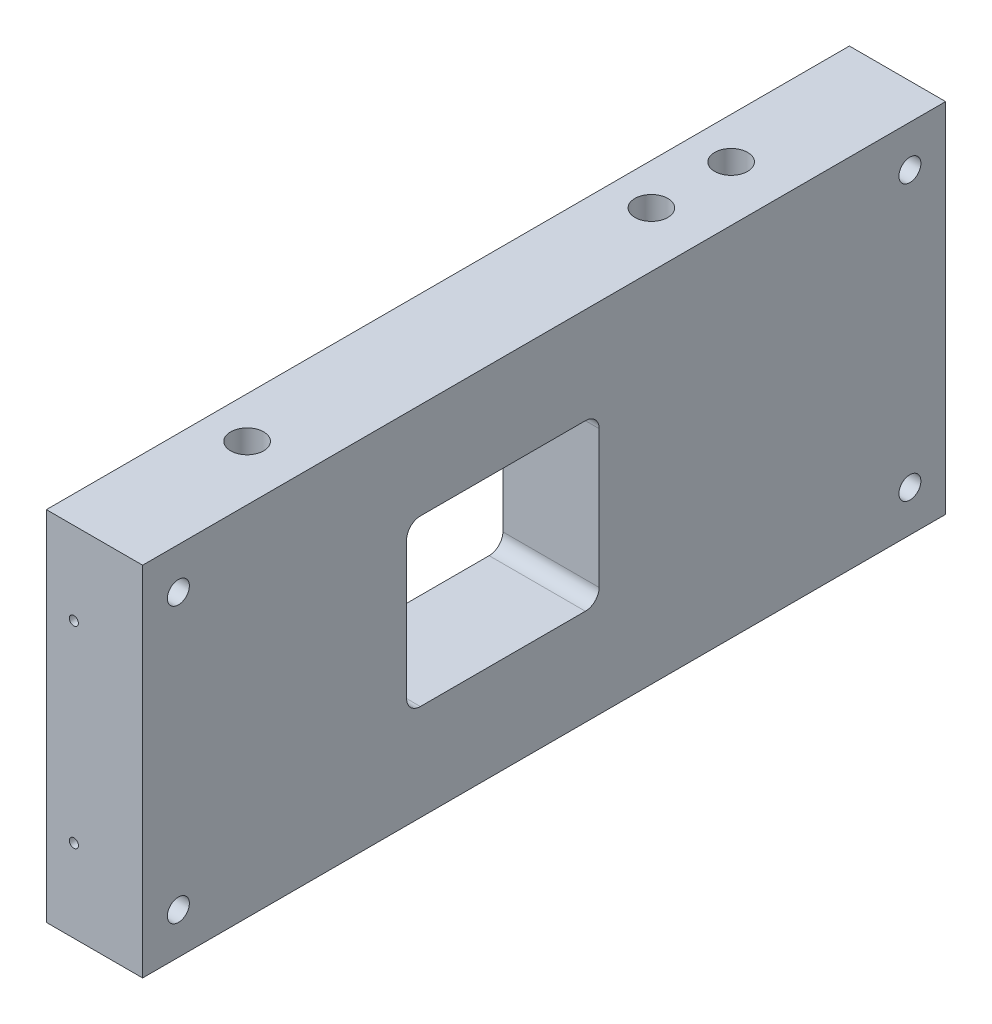
SolidWorks part; units mm, degrees
material "6063-T6"
ref_plane "Front Plane" through (0, 0, 0) normal (0, 0, 1) x (1, 0, 0)
ref_plane "Top Plane" through (0, 0, 0) normal (0, 1, 0) x (1, 0, 0)
ref_plane "Right Plane" through (0, 0, 0) normal (1, 0, 0) x (0, 0, -1)
sketch "Sketch2" plane through (0, 0, 0) normal (1, 0, 0) x (0, 0, -1)
  line L5 (0, 65) -> (191, 65)
  line L6 (0, 65) -> (0, -65)
  line L7 (0, -65) -> (191, -65)
  line L8 (191, 65) -> (191, -65)
  dimension "D1" = 65
  dimension "D2" = 130
  dimension "D3" = 191
extrude "Boss-Extrude1" add sketch "Sketch2" along normal blind 35
sketch "Sketch10" plane through (0, 0, 0) normal (0, 0, 1) x (1, 0, 0)
  line L1 (0, -65) -> (35, -65)
  line L2 (0, -65) -> (0, 65)
  line L3 (0, 65) -> (35, 65)
  line L4 (35, -65) -> (35, 65)
extrude "Boss-Extrude2" add sketch "Sketch10" along normal blind 101
sketch "Sketch4" plane through (0, 0, 0) normal (0, 0, 1) x (1, 0, 0)
  line L0 (0, 0) -> (60, 0)
  line L4 (0, 23.5) -> (8, 23.5)
  line L5 (8, 23.5) -> (8, 20)
  line L6 (8, 20) -> (18, 13.5)
  line L7 (18, 13.5) -> (22, 13.5)
  line L8 (22, 13.5) -> (22, 26)
  line L9 (22, 26) -> (27, 26)
  line L10 (27, 26) -> (27, 27)
  line L11 (27, 27) -> (51, 27)
  line L12 (51, 27) -> (51, 31)
  line L13 (51, 31) -> (60, 31)
  line L14 (0, 23.5) -> (0, 0)
  line L16 (60, 31) -> (60, 0)
  dimension "D1" = 5
  dimension "D2" = 1
  dimension "D3" = 13.5
  dimension "D4" = 26
  dimension "D5" = 29
  dimension "D6" = 8
  dimension "D7" = 3.5
  dimension "D8" = 14
  dimension "D9" = 4
  dimension "D10" = 23.5
sketch "Sketch6" plane through (0, 0, 0) normal (-1, 0, 0) x (0, 0, 1)
  point P0 (0, 0)
sketch "Sketch15" plane through (0, 0, 101) normal (0, 0, 1) x (1, 0, 0)
  line L0 (0, 65) -> (0, -65) construction
  line L1 (10, 35) -> (40, 35)
  line L2 (10, 35) -> (10, -35)
  line L3 (10, -35) -> (40, -35)
  line L4 (40, 35) -> (40, -35)
  line L5 (35, 65) -> (0, 65) construction
  line L6 (0, -65) -> (35, -65) construction
  dimension "D1" = 10
  dimension "D2" = 30
  dimension "D3" = 30
  dimension "D4" = 30
sketch "Sketch16" plane through (0, 0, -191) normal (0, 0, -1) x (-1, 0, 0)
  line L0 (-35, 65) -> (0, 65) construction
  line L1 (-40, 35) -> (-10, 35)
  line L2 (-40, 35) -> (-40, -35)
  line L3 (-40, -35) -> (-10, -35)
  line L4 (-10, 35) -> (-10, -35)
  line L5 (0, -65) -> (0, 65) construction
  line L6 (-35, -65) -> (0, -65) construction
  dimension "D1" = 30
  dimension "D2" = 30
  dimension "D3" = 10
  dimension "D4" = 30
hole_wizard "Tap Drill for M4 Tap2" positions "Sketch19" profile "Sketch20" hole size "M4" standard "ISO"
sketch "Sketch19" plane through (0, 0, -191) normal (0, 0, -1) x (-1, 0, 0)
  point P0 (-40, 35)
  point P3 (-10, 35)
  point P6 (-10, -35)
  point P9 (-40, -35)
sketch "Sketch20" plane through (40, 35, -191) normal (1, 0, 0) x (0, 1, 0)
  line L0 (0, 0) -> (0, 6.9914)
  line L1 (0, 6.9914) -> (1.65, 6)
  line L2 (1.65, 6) -> (1.65, 0)
  line L5 (1.65, 0) -> (0, 0)
  line L10 (0, 6.9914) -> (-1.65, 6) construction
  line L11 (0, -6.35) -> (0, 107.95) construction
  dimension "Hole Dia." = 3.3
  dimension "Hole Depth" = 6
  dimension "Drill Angle" = 118
hole_wizard "Tap Drill for M4 Tap3" positions "Sketch21" profile "Sketch22" hole size "M4" standard "ISO"
sketch "Sketch21" plane through (0, 0, 101) normal (0, 0, 1) x (1, 0, 0)
  point P0 (10, 35)
  point P3 (40, 35)
  point P6 (40, -35)
  point P9 (10, -35)
sketch "Sketch22" plane through (10, 35, 101) normal (1, 0, 0) x (0, -1, 0)
  line L0 (0, 0) -> (0, 6.9914)
  line L1 (0, 6.9914) -> (1.65, 6)
  line L2 (1.65, 6) -> (1.65, 0)
  line L5 (1.65, 0) -> (0, 0)
  line L10 (0, 6.9914) -> (-1.65, 6) construction
  line L11 (0, -6.35) -> (0, 107.95) construction
  dimension "Hole Dia." = 3.3
  dimension "Hole Depth" = 6
  dimension "Drill Angle" = 118
sketch "Sketch23" plane through (0, 0, 0) normal (-1, 0, 0) x (0, 0, 1)
  line L0 (-65, 25) -> (-65, -25)
  line L1 (-60, 30) -> (0, 30)
  line L2 (-60, -30) -> (0, -30)
  line L3 (5, 25) -> (5, -25)
  arc A1 (-65, -25) -> (-60, -30) centre (-60, -25) ccw
  arc A2 (0, -30) -> (5, -25) centre (0, -25) ccw
  arc A3 (0, 30) -> (5, 25) centre (0, 25) cw
  arc A4 (-60, 30) -> (-65, 25) centre (-60, 25) ccw
  point P1 (0, 0)
  dimension "D1" = 5
  dimension "D2" = 70
  dimension "D3" = 65
extrude "Cut-Extrude1" cut sketch "Sketch23" against normal through all
sketch "Sketch24" plane through (0, 0, 0) normal (-1, 0, 0) x (0, 0, 1)
  line L0 (0, 0) -> (0, 42.2578) construction
  line L1 (35, 25) -> (55, 25)
  line L2 (35, 25) -> (35, -25)
  line L3 (35, -25) -> (55, -25)
  line L4 (55, 25) -> (55, -25)
  line L5 (-55, 25) -> (-55, -25)
  line L6 (-35, -25) -> (-55, -25)
  line L7 (-35, 25) -> (-35, -25)
  line L8 (-35, 25) -> (-55, 25)
  point P4 (35, 0)
  dimension "D1" = 20
  dimension "D2" = 50
  dimension "D3" = 35
  dimension "D4" = 0
sketch "Sketch28" plane through (35, 0, 0) normal (1, 0, 0) x (0, 0, -1)
  line L0 (191, 65) -> (-101, 65) construction
  line L1 (191, -65) -> (191, 65) construction
  line L2 (-101, -65) -> (191, -65) construction
  line L3 (-101, -65) -> (-101, 65) construction
  point P0 (-88, 50)
  point P1 (-88, -50)
  point P2 (178, -50)
  point P3 (178, 50)
  point P12 (178, -50)
  dimension "D1" = 15
  dimension "D2" = 13
  dimension "D3" = 15
  dimension "D4" = 13
hole_wizard "Ø8.0mm Dowel Hole1" positions "Sketch29" profile "Sketch30" hole size "Ø8.0" standard "ISO" end condition through all
sketch "Sketch29" plane through (35, 0, 0) normal (1, 0, 0) x (0, 0, -1)
  point P0 (-88, 50)
  point P3 (-88, -50)
  point P6 (178, -50)
  point P9 (178, 50)
sketch "Sketch30" plane through (35, 50, 88) normal (0, 1, 0) x (0, 0, -1)
  line L0 (0, 0) -> (0, 35)
  line L1 (0, 35) -> (4, 35)
  line L2 (4, 35) -> (4, 0)
  line L5 (4, 0) -> (0, 0)
  line L11 (0, -6.35) -> (0, 107.95) construction
  dimension "Thru Hole Dia." = 8
  dimension "Thru Hole Depth" = 35
sketch "Sketch31" plane through (35, 0, 0) normal (1, 0, 0) x (0, 0, -1)
  line L0 (176, 25) -> (176, -25)
  line L1 (171, -30) -> (131, -30)
  line L2 (126, -25) -> (126, 25)
  line L3 (131, 30) -> (171, 30)
  line L4 (191, 35) -> (191, -35) construction
  line L5 (191, 65) -> (-101, 65) construction
  line L6 (-101, -65) -> (191, -65) construction
  line L7 (161, 50) -> (-71, 50)
  line L8 (-71, 50) -> (-71, 40)
  line L9 (-71, 40) -> (161, 40)
  line L10 (161, 40) -> (161, 50)
  line L11 (191, -65) -> (191, 65) construction
  line L12 (-101, 65) -> (-101, -65) construction
  line L13 (0, 0) -> (24.0944, 0) construction
  line L18 (161, -40) -> (161, -50)
  line L19 (-71, -40) -> (161, -40)
  line L20 (-71, -50) -> (-71, -40)
  line L21 (161, -50) -> (-71, -50)
  arc A0 (156, 50) -> (160.9957, 44.7929) centre (156, 45) cw
  arc A1 (-66, 50) -> (-66, 40) centre (-66, 45) ccw
  arc A2 (-66, -50) -> (-66, -40) centre (-66, -45) cw
  arc A3 (156, -50) -> (160.9957, -44.7929) centre (156, -45) ccw
  arc A4 (176, -25) -> (171, -30) centre (171, -25) cw
  arc A5 (131, -30) -> (126, -25) centre (131, -25) cw
  arc A6 (126, 25) -> (131, 30) centre (131, 25) cw
  arc A7 (176, 25) -> (171, 30) centre (171, 25) ccw
  point P39 (176, -30)
  point P42 (126, -30)
  point P45 (126, 30)
  point P48 (176, 30)
  dimension "D11" = 5
  dimension "D1" = 15
  dimension "D2" = 50
  dimension "D3" = 35
  dimension "D4" = 35
  dimension "D5" = 35
  dimension "D6" = 35
  dimension "D7" = 15
  dimension "D8" = 10
  dimension "D9" = 30
  dimension "D10" = 30
sketch "Sketch32" plane through (35, 0, 0) normal (1, 0, 0) x (0, 0, -1)
  line L0 (-101, 35) -> (-101, -35) construction
  line L1 (-81, 30) -> (-20, 30)
  line L2 (-86, 25) -> (-86, -25)
  line L3 (-81, -30) -> (-20, -30)
  line L4 (-15, 25) -> (-15, -25)
  line L5 (80, 30) -> (126, 30)
  line L6 (75, 25) -> (75, -25)
  line L7 (80, -30) -> (126, -30)
  line L8 (131, 25) -> (131, -25)
  line L9 (-5, -25) -> (-5, 25) construction
  line L12 (-66, 40) -> (171, 40) construction
  line L13 (-66, -40) -> (171, -40) construction
  line L15 (65, 25) -> (65, -25) construction
  line L17 (141, -25) -> (141, 25) construction
  arc A0 (75, -25) -> (80, -30) centre (80, -25) ccw
  arc A1 (126, -30) -> (131, -25) centre (126, -25) ccw
  arc A2 (126, 30) -> (131, 25) centre (126, 25) cw
  arc A3 (80, 30) -> (75, 25) centre (80, 25) ccw
  arc A4 (-86, -25) -> (-81, -30) centre (-81, -25) ccw
  arc A5 (-20, -30) -> (-15, -25) centre (-20, -25) ccw
  arc A6 (-20, 30) -> (-15, 25) centre (-20, 25) cw
  arc A7 (-81, 30) -> (-86, 25) centre (-81, 25) ccw
  point P18 (103, -30)
  dimension "D9" = 5
  dimension "D1" = 15
  dimension "D2" = 10
  dimension "D3" = 10
  dimension "D4" = 10
  dimension "D5" = 10
  dimension "D6" = 10
  dimension "D7" = 10
  dimension "D8" = 10
sketch "Sketch35" plane through (0, 0, 0) normal (-1, 0, 0) x (0, 0, 1)
  line L0 (-65, 25) -> (-65, -25) construction
  line L1 (-151, 55) -> (-85, 55)
  line L2 (-161, 45) -> (-161, -45)
  line L3 (-151, -55) -> (-85, -55)
  line L4 (-75, 45) -> (-75, -45)
  line L5 (25, 55) -> (61, 55)
  line L6 (15, 45) -> (15, -45)
  line L7 (25, -55) -> (61, -55)
  line L8 (71, 45) -> (71, -45)
  line L9 (-191, -65) -> (-191, 65) construction
  line L10 (-191, 65) -> (101, 65) construction
  line L11 (101, -65) -> (-191, -65) construction
  line L12 (101, 65) -> (101, -65) construction
  line L13 (5, -25) -> (5, 25) construction
  arc A0 (61, 55) -> (71, 45) centre (61, 45) cw
  arc A1 (61, -55) -> (71, -45) centre (61, -45) ccw
  arc A2 (15, -45) -> (25, -55) centre (25, -45) ccw
  arc A3 (25, 55) -> (15, 45) centre (25, 45) ccw
  arc A4 (-85, -55) -> (-75, -45) centre (-85, -45) ccw
  arc A5 (-85, 55) -> (-75, 45) centre (-85, 45) cw
  arc A6 (-161, -45) -> (-151, -55) centre (-151, -45) ccw
  arc A7 (-151, 55) -> (-161, 45) centre (-151, 45) ccw
  dimension "D9" = 10
  dimension "D1" = 10
  dimension "D2" = 30
  dimension "D3" = 10
  dimension "D4" = 10
  dimension "D5" = 10
  dimension "D6" = 10
  dimension "D7" = 30
  dimension "D8" = 10
extrude "Cut-Extrude3" cut sketch "Sketch35" against normal offset from surface (30 mm away) 5 up to face at (35, 50, 84)
sketch "Sketch36" plane through (0, -55, 0) normal (0, 1, 0) x (1, 0, 0)
  line L3 (0, 151) -> (0, 85) construction
  line L4 (0, -25) -> (0, -61) construction
  line L5 (35, 191) -> (0, 191) construction
  line L6 (10, -101) -> (40, -101) construction
  point P0 (15, 133)
  point P1 (15, 104)
  point P2 (15, -43)
  dimension "D1" = 58
  dimension "D2" = 29
  dimension "D3" = 58
  dimension "D4" = 15
  dimension "D5" = 15
  dimension "D6" = 15
hole_wizard "Ø8.0mm Dowel Hole2" positions "Sketch37" profile "Sketch38" hole size "Ø8.0" standard "ISO"
sketch "Sketch37" plane through (0, -55, 0) normal (0, 1, 0) x (1, 0, 0)
  point P0 (15, 133)
  point P3 (15, 104)
  point P6 (15, -43)
sketch "Sketch38" plane through (15, -55, -133) normal (1, 0, 0) x (0, 0, 1)
  line L0 (0, 0) -> (0, 12.4034)
  line L1 (0, 12.4034) -> (4, 10)
  line L2 (4, 10) -> (4, 0)
  line L5 (4, 0) -> (0, 0)
  line L10 (0, 12.4034) -> (-4, 10) construction
  line L11 (0, -6.35) -> (0, 107.95) construction
  dimension "Hole Dia." = 8
  dimension "Hole Depth" = 10
  dimension "Drill Angle" = 118
hole_wizard "Ø12.0mm Dowel Hole1" positions "Sketch40" profile "Sketch41" hole size "Ø12.0" standard "ISO"
sketch "Sketch40" plane through (0, 65, 0) normal (0, 1, 0) x (1, 0, 0)
  point P0 (15, 133)
  point P3 (15, 104)
  point P6 (15, -43)
sketch "Sketch41" plane through (15, 65, -133) normal (1, 0, 0) x (0, 0, 1)
  line L0 (0, 0) -> (0, 13.6052)
  line L1 (0, 13.6052) -> (6, 10)
  line L2 (6, 10) -> (6, 0)
  line L5 (6, 0) -> (0, 0)
  line L10 (0, 13.6052) -> (-6, 10) construction
  line L11 (0, -6.35) -> (0, 107.95) construction
  dimension "Hole Dia." = 12
  dimension "Hole Depth" = 10
  dimension "Drill Angle" = 118
